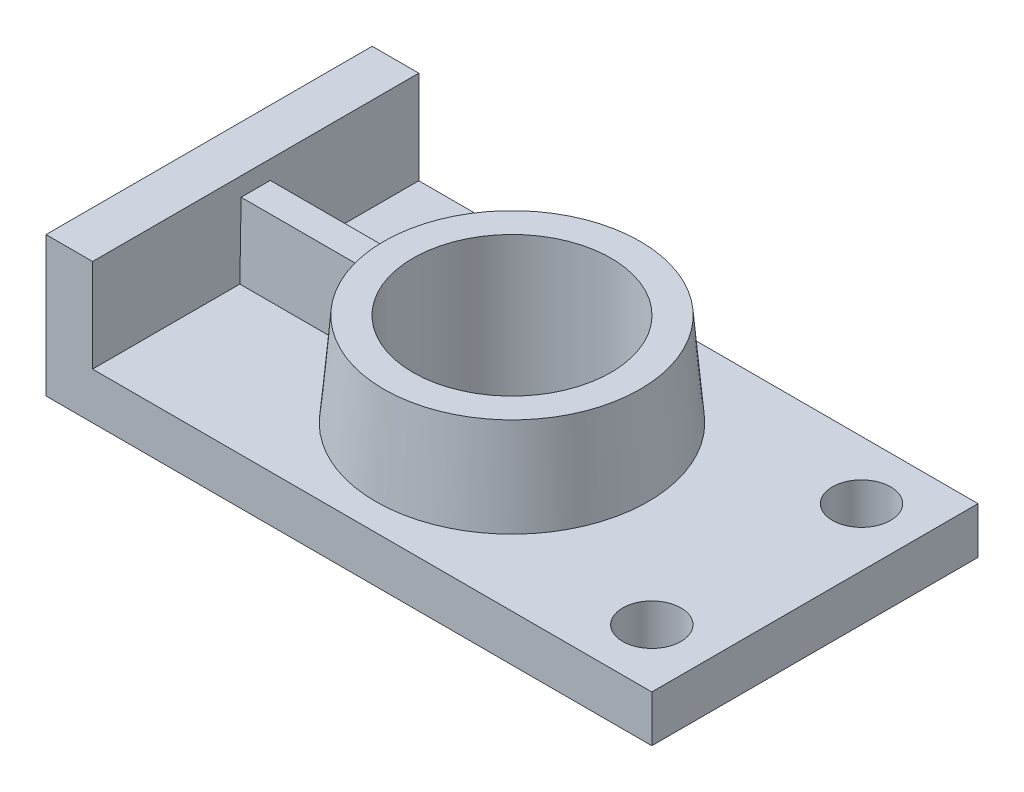
SolidWorks part; units mm, degrees
ref_plane "Plane1" through (0, 0, 0) normal (0, 0, 1) x (1, 0, 0)
ref_plane "Plane2" through (0, 0, 0) normal (0, 1, 0) x (1, 0, 0)
ref_plane "Plane3" through (0, 0, 0) normal (1, 0, 0) x (0, 0, -1)
sketch "Sketch1" plane through (0, 0, 0) normal (0, 0, 1) x (1, 0, 0)
  line L0 (0, 38.1) -> (0, 0)
  line L1 (0, 0) -> (165.1, 0)
  dimension "D1" = 165.1
  dimension "D2" = 38.1
extrude "Base-Extrude-Thin" add sketch "Sketch1" against normal blind 88.9 thin thin type one direction reverse wall 12.7
sketch "Sketch2" plane through (0, 38.1, 0) normal (0, 1, 0) x (-1, 0, 0)
  line L0 (0, -88.9) -> (-165.1, 0) construction
  circle A0 centre (-82.55, -44.45) radius 34.925
  dimension "D1" = 69.85
extrude "Boss-Extrude1" add sketch "Sketch2" against normal up to next draft 5 draft outward yes
sketch "Sketch3" plane through (0, 38.1, 0) normal (0, 1, 0) x (-1, 0, 0)
  circle A0 centre (-82.55, -44.45) radius 26.9875
  dimension "D1" = 53.975
extrude "Cut-Extrude1" cut sketch "Sketch3" against normal through all
sketch "Sketch4" plane through (0, 12.7, 0) normal (0, 1, 0) x (-1, 0, 0)
  line L0 (-12.7, 0) -> (-165.1, 0) construction
  line L1 (-165.1, -88.9) -> (-165.1, 0) construction
  line L2 (-12.7, -88.9) -> (-165.1, -88.9) construction
  circle A0 centre (-149.225, -15.875) radius 7.9375
  circle A1 centre (-149.225, -73.025) radius 7.9375
  dimension "D1" = 15.875
  dimension "D2" = 15.875
  dimension "D3" = 15.875
  dimension "D4" = 15.875
extrude "Cut-Extrude2" cut sketch "Sketch4" against normal through all
ref_plane "Rib Plane" through (0, 33.02, 0) normal (0, 1, 0) x (-1, 0, 0)
sketch "Sketch5" plane through (0, 33.02, 0) normal (0, 1, 0) x (-1, 0, 0)
  line L0 (-42.7788, -44.45) -> (-21.6504, -44.45)
rib "Rib1" sketch "Sketch5" sketch "Sketch5" thickness 7.9375 extrusion direction normal to sketch draft on yes draft angle 1 parameters "D1"=7.9375, "D3"=1
